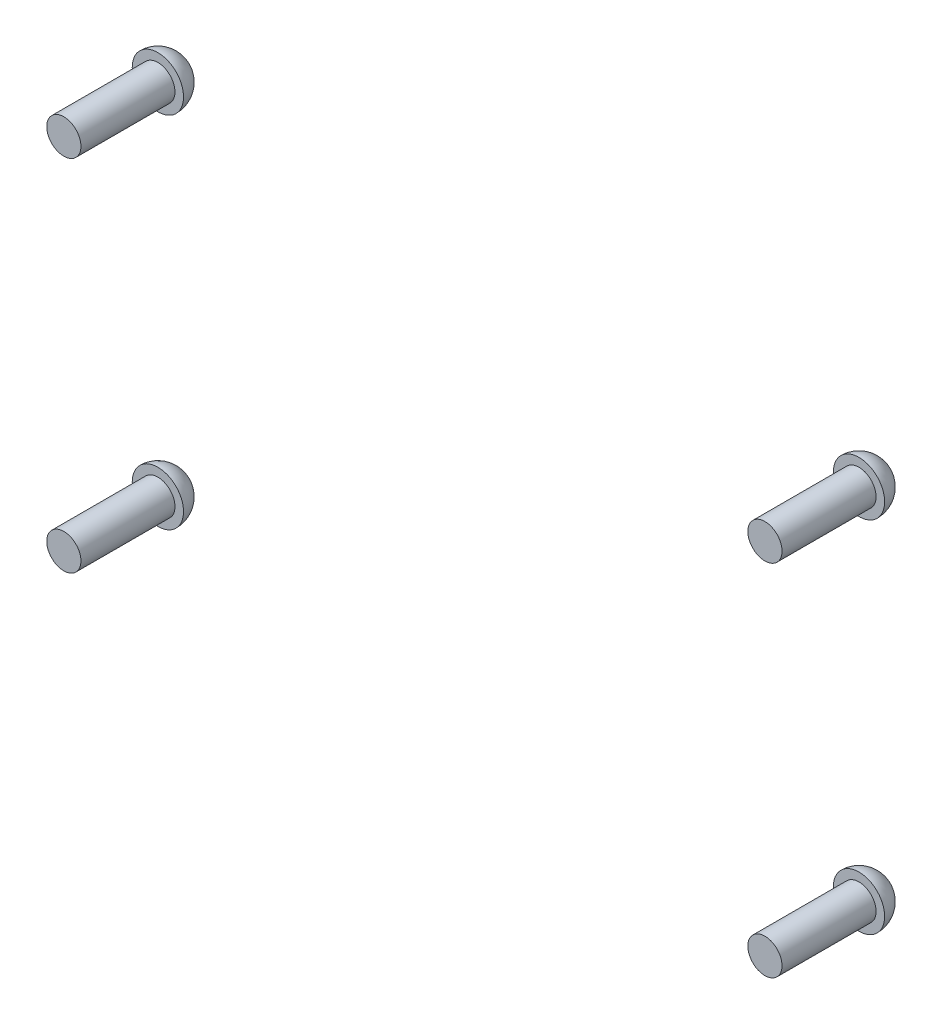
SolidWorks part; units mm, degrees
ref_plane "前视基准面" through (0, 0, 0) normal (0, 0, 1) x (1, 0, 0)
ref_plane "上视基准面" through (0, 0, 0) normal (0, 1, 0) x (1, 0, 0)
ref_plane "右视基准面" through (0, 0, 0) normal (1, 0, 0) x (0, 0, -1)
other "Configuration Table"
sketch "草图1" plane through (0, 0, 0) normal (0, 0, 1) x (1, 0, 0)
  circle A0 centre (-45.3687, 33.7199) radius 10
  circle A1 centre (364.6313, 33.7199) radius 10
  circle A2 centre (-45.3687, -176.2801) radius 10
  circle A3 centre (364.6313, -176.2801) radius 10
  circle A4 centre (-45.3687, 33.7199) radius 15
  circle A5 centre (364.6313, 33.7199) radius 15
  circle A6 centre (364.6313, -176.2801) radius 15
  circle A7 centre (-45.3687, -176.2801) radius 15
  point P8 (0, 0)
  point P9 (0, 0)
  point P18 (0, 0)
  dimension "D1" = 5
  dimension "D3" = 410
  dimension "D4" = 210
  dimension "D2" = 5
extrude "凸台-拉伸3" add sketch "草图1" along normal blind 55 contours A2 | A0 | A1 | A3
sketch "草图6" plane through (0, 0, 0) normal (0, 0, -1) x (-1, 0, 0)
  circle A2 centre (-364.6313, 33.7199) radius 15
  circle A3 centre (-364.6313, 33.7199) radius 15
  circle A5 centre (45.3687, -176.2801) radius 15
  circle A6 centre (45.3687, -176.2801) radius 15
  circle A8 centre (45.3687, 33.7199) radius 15
  circle A9 centre (45.3687, 33.7199) radius 15
  circle A11 centre (-364.6313, -176.2801) radius 15
  circle A12 centre (-364.6313, -176.2801) radius 15
  dimension "D1" = 5
  dimension "D2" = 5
  dimension "D3" = 5
  dimension "D4" = 5
extrude "凸台-拉伸5" add sketch "草图6" along normal blind 15 contours A9 | A6 | A12 | A3
fillet "圆角16" radius 14.99 1 edges at (349.6313, -176.2801, -15)
fillet "圆角17" radius 14.99 1 edges at (-60.3687, -176.2801, -15)
fillet "圆角18" radius 14.99 1 edges at (-60.3687, 33.7199, -15)
fillet "圆角19" radius 14.99 1 edges at (349.6313, 33.7199, -15)
